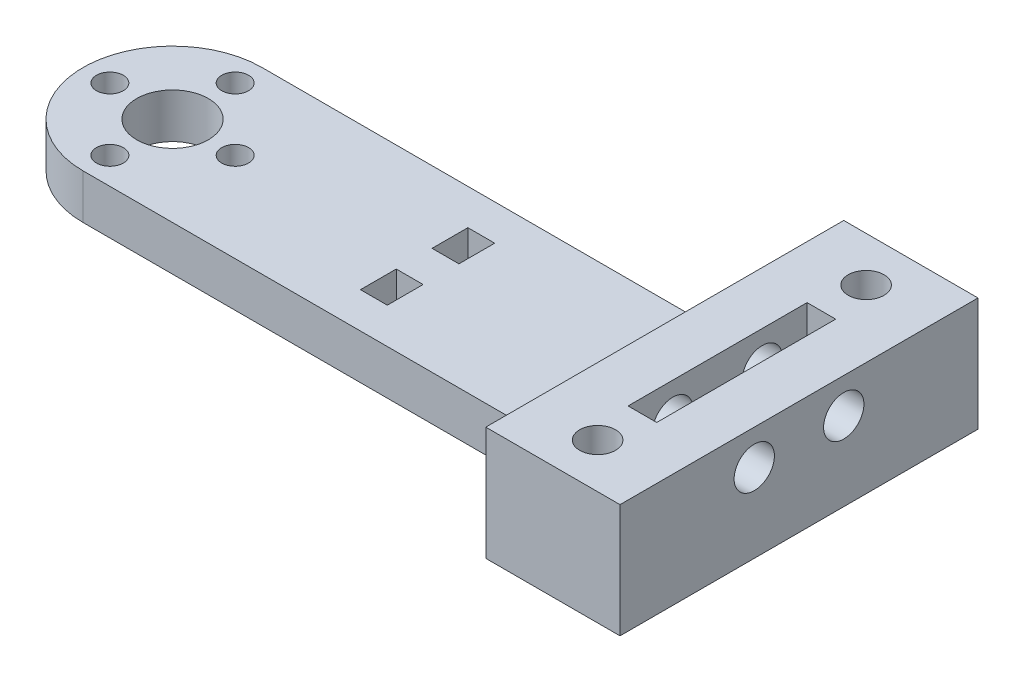
SolidWorks part; units mm, degrees
material "PF"
ref_plane "前视基准面" through (0, 0, 0) normal (0, 0, 1) x (1, 0, 0)
ref_plane "上视基准面" through (0, 0, 0) normal (0, 1, 0) x (1, 0, 0)
ref_plane "右视基准面" through (0, 0, 0) normal (1, 0, 0) x (0, 0, -1)
sketch "草图1" plane through (0, 0, 0) normal (0, 1, 0) x (1, 0, 0)
  line L1 (-41.2, 20) -> (78.8, 20)
  line L3 (-41.2, 0) -> (78.8, 0)
  line L4 (78.8, 20) -> (78.8, 0)
  arc A0 (-41.2, 20) -> (-41.2, 0) centre (-41.2, 10) ccw
  dimension "D1" = 20
  dimension "D2" = 120
extrude "凸台-拉伸1" add sketch "草图1" along normal blind 5
sketch "草图2" plane through (0, 5, 0) normal (0, 1, 0) x (1, 0, 0)
  line L0 (-41.2, 20) -> (-41.2, 0) construction
  line L1 (-41.2, 17) -> (-41.2, 3)
  circle A0 centre (-41.2, 3) radius 1.5
  circle A1 centre (-48.2, 10) radius 1.5
  circle A2 centre (-41.2, 17) radius 1.5
  circle A3 centre (-34.2, 10) radius 1.5
  circle A4 centre (-41.2, 10) radius 4
  point P7 (-41.2, 10)
  dimension "D1" = 4
extrude "切除-拉伸1" cut sketch "草图2" against normal blind 5 contours A1 | A2 L0 L1 | L0 A2 L1 | A3 | L1 L0 A0 | L0 L1 A0 | A4
sketch "草图3" plane through (0, 5, 0) normal (0, 1, 0) x (1, 0, 0)
  line L0 (-51.2, 10) -> (-14.2, 10) construction
  line L1 (-14.2, 20) -> (-14.2, 0) construction
  line L2 (78.8, 20) -> (-41.2, 20) construction
  line L3 (-41.2, 0) -> (78.8, 0) construction
  line L4 (-14.2, 12) -> (-14.2, 8)
  line L5 (-14.2, 12) -> (-14.2, 16)
  line L6 (-14.2, 12) -> (-11.2, 12)
  line L7 (-14.2, 16) -> (-11.2, 16)
  line L8 (-11.2, 12) -> (-11.2, 16)
  line L9 (-14.2, 8) -> (-14.2, 4)
  line L10 (-14.2, 8) -> (-11.2, 8)
  line L11 (-14.2, 4) -> (-11.2, 4)
  line L12 (-11.2, 8) -> (-11.2, 4)
  arc A0 (-41.2, 20) -> (-41.2, 0) centre (-41.2, 10) ccw construction
  circle A1 centre (-41.2, 10) radius 4 construction
  point P14 (-14.2, 10)
  dimension "D4" = 27
  dimension "D1" = 4
  dimension "D2" = 4
  dimension "D3" = 3
extrude "切除-拉伸2" cut sketch "草图3" against normal blind 5 contours L5 L6 L8 L7 | L9 L10 L12 L11
sketch "草图4" plane through (0, 5, 0) normal (0, 1, 0) x (1, 0, 0)
  line L0 (78.8, 10) -> (69.3, 10) construction
  line L1 (78.8, 0) -> (78.8, 20) construction
  line L2 (78.8, 20) -> (78.8, 0)
  line L3 (69.3, 10) -> (76.7246, 17.4246)
  line L4 (69.3, 10) -> (62.3, 10)
  line L5 (69.3, 17) -> (69.3, 3) construction
  line L6 (69.3, 3) -> (69.3, 10) construction
  line L7 (61.8754, 17.4246) -> (69.3, 10) construction
  line L8 (69.3, 10) -> (76.7246, 2.5754) construction
  line L9 (76.7246, 2.5754) -> (69.3, 10) construction
  line L10 (61.8754, 2.5754) -> (69.3, 10) construction
  line L11 (61.8754, 2.5754) -> (69.3, 10) construction
  line L12 (69.3, 10) -> (52.3, 10) construction
  line L13 (52.3, 20) -> (52.3, 0)
  line L14 (-41.2, 0) -> (78.8, 0) construction
  line L15 (52.3, 12) -> (52.3, 16)
  line L16 (52.3, 12) -> (49.3, 12)
  line L17 (52.3, 16) -> (49.3, 16)
  line L18 (49.3, 12) -> (49.3, 16)
  line L19 (-14.2, 12) -> (-11.2, 12) construction
  line L20 (52.3, 4) -> (49.3, 4)
  line L21 (49.3, 8) -> (49.3, 4)
  line L22 (52.3, 8) -> (49.3, 8)
  line L23 (52.3, 8) -> (52.3, 4)
  circle A0 centre (76.7246, 17.4246) radius 1.1
  circle A1 centre (76.7246, 2.5754) radius 1.1
  circle A2 centre (61.8754, 2.5754) radius 1.1
  circle A3 centre (61.8754, 17.4246) radius 1.1
  circle A4 centre (62.3, 10) radius 1.1
  circle A5 centre (69.3, 17) radius 1.1
  circle A6 centre (76.3, 10) radius 1.1
  circle A7 centre (69.3, 3) radius 1.1
  circle A8 centre (69.3, 10) radius 4
  point P29 (52.3, 10)
  dimension "D2" = 4
  dimension "D3" = 4
  dimension "D8" = 8
  dimension "D1" = 9.5
  dimension "D4" = 7
  dimension "D5" = 17
  dimension "D6" = 3
  dimension "D7" = 4
extrude "切除-拉伸4" cut sketch "草图4" against normal blind 10
sketch "草图5" plane through (0, 5, 0) normal (0, 1, 0) x (1, 0, 0)
  line L0 (-41.2, 10) -> (28.8, 10) construction
  line L1 (78.8, 20) -> (78.8, 0)
  line L2 (78.8, 20) -> (28.8, 20)
  line L3 (78.8, 0) -> (28.8, 0)
  line L4 (28.8, 20) -> (28.8, 0)
  dimension "D1" = 70
extrude "切除-拉伸5" cut sketch "草图5" against normal blind 10
sketch "草图6" plane through (0, 5, 0) normal (0, 1, 0) x (1, 0, 0)
  line L0 (28.8, 20) -> (28.8, 0)
  line L1 (28.8, 20) -> (13.8, 20)
  line L2 (28.8, 0) -> (13.8, 0)
  line L3 (13.8, 20) -> (13.8, 0)
  dimension "D1" = 15
extrude "凸台-拉伸2" add sketch "草图6" along normal blind 7.7
sketch "草图7" plane through (28.8, 0, 0) normal (1, 0, 0) x (0, 0, -1)
  line L0 (0, 0) -> (0, 12.7) construction
  line L1 (20, 0) -> (0, 0) construction
  line L2 (10, 12.7) -> (10, 0) construction
  line L3 (0, 12.7) -> (20, 12.7) construction
  circle A0 centre (5, 8.8) radius 2.25
  circle A1 centre (15, 8.8) radius 2.25
  dimension "D1" = 5
  dimension "D2" = 8.8
extrude "切除-拉伸6" cut sketch "草图7" against normal blind 20
sketch "草图8" plane through (0, 12.7, 0) normal (0, 1, 0) x (1, 0, 0)
  line L0 (28.8, 30) -> (28.8, -10)
  line L1 (28.8, 30) -> (13.8, 30)
  line L2 (28.8, -10) -> (13.8, -10)
  line L3 (13.8, 30) -> (13.8, -10)
  line L4 (28.8, 0) -> (28.8, 20) construction
  line L5 (13.8, 20) -> (13.8, 0) construction
  line L6 (28.8, 10) -> (13.8, 10) construction
  line L8 (28.8, 20) -> (13.8, 20)
  line L9 (13.8, 20) -> (13.8, 0)
  line L10 (13.8, 0) -> (28.8, 0)
  circle A1 centre (21.3, -5) radius 2
  circle A2 centre (21.3, 25) radius 2
  point P10 (28.8, 10)
  dimension "D2" = 5
  dimension "D3" = 7.5
  dimension "D1" = 40
extrude "凸台-拉伸3" add sketch "草图8" against normal blind 12.7
sketch "草图9" plane through (0, 12.7, 0) normal (0, 1, 0) x (1, 0, 0)
  line L0 (21.3, 25) -> (21.3, -5) construction
  line L1 (21.3, -5) -> (21.3, 10) construction
  line L2 (21.3, 10) -> (28.8, 10) construction
  line L3 (28.8, -10) -> (28.8, 30) construction
  line L4 (22.9, 20) -> (22.9, 0)
  line L5 (22.9, 20) -> (19.7, 20)
  line L6 (22.9, 0) -> (19.7, 0)
  line L7 (19.7, 20) -> (19.7, 0)
  line L8 (21.3, 0) -> (21.3, 20) construction
  line L9 (22.9, 10) -> (19.7, 10) construction
  dimension "D1" = 20
  dimension "D2" = 3.2
extrude "切除-拉伸7" cut sketch "草图9" against normal blind 8
